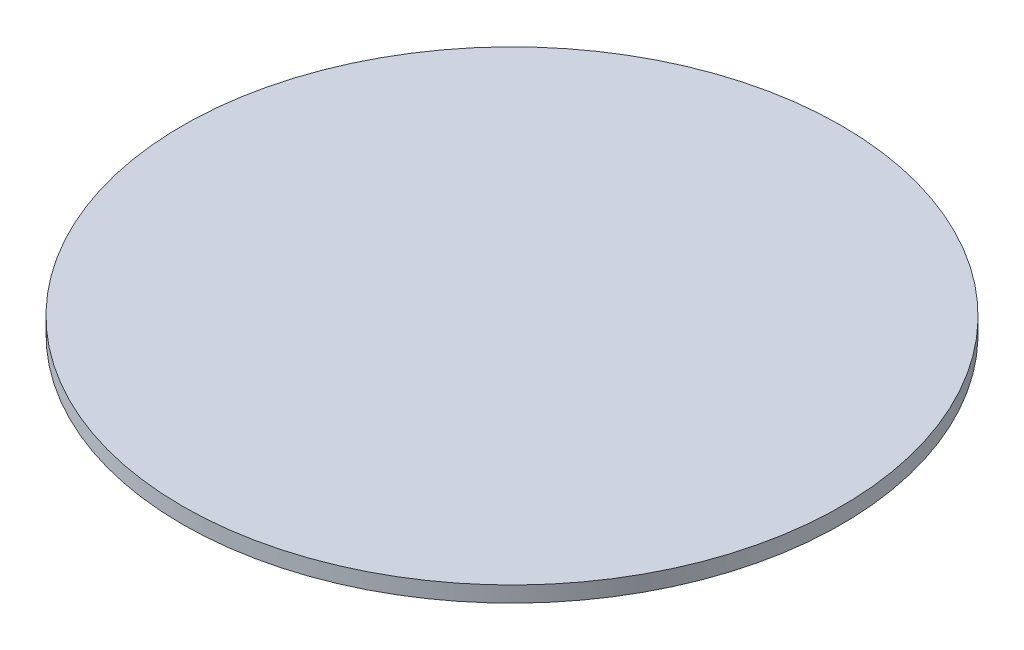
SolidWorks part; units mm, degrees
ref_plane "Front Plane" through (0, 0, 0) normal (0, 0, 1) x (1, 0, 0)
ref_plane "Top Plane" through (0, 0, 0) normal (0, 1, 0) x (1, 0, 0)
ref_plane "Right Plane" through (0, 0, 0) normal (1, 0, 0) x (0, 0, -1)
sketch "Front" plane through (0, 0, 0) normal (0, 0, 1) x (1, 0, 0)
  line L0 (0, 0) -> (0, 13458.9015) construction
  line L1 (0, 0) -> (13458.9015, 0) construction
  line L3 (-20.95, -0.5) -> (0, -0.5)
  line L4 (-20.95, -0.5) -> (-20.95, 0.5)
  line L5 (-20.95, 0.5) -> (0, 0.5)
  line L6 (0, -0.5) -> (0, 0.5)
  line L7 (-20.95, -0.5) -> (0, 0.5) construction
  line L8 (-20.95, 0.5) -> (0, -0.5) construction
  point P5 (-10.475, 0)
  dimension "D1" = 41.9
  dimension "D2" = 1
sketch "Right" plane through (0, 0, 0) normal (1, 0, 0) x (0, 0, -1)
  line L0 (0, 0) -> (0, 50000) construction
  line L1 (0, 0) -> (50000, 0) construction
revolve "Base" add sketch "Front" angle 360 about L0
sketch "Sketch1" plane through (0, -0.5, 0) normal (0, -1, 0) x (1, 0, 0)
  line L0 (0, 0) -> (167.4187, 0) construction
  line L1 (-2, 14.5) -> (-2, 15.5)
  line L2 (-2, 14.5) -> (2, 14.5)
  line L3 (2, 14.5) -> (2, 15.5)
  line L4 (-2, 15.5) -> (2, 15.5)
  line L5 (-2, 14.5) -> (2, 15.5) construction
  line L6 (2, 14.5) -> (-2, 15.5) construction
  line L7 (0, 0) -> (0, -167.4187) construction
  line L8 (2, -14.5) -> (-2, -15.5) construction
  line L9 (-2, -14.5) -> (2, -15.5) construction
  line L10 (-2, -15.5) -> (2, -15.5)
  line L11 (2, -14.5) -> (2, -15.5)
  line L12 (-2, -14.5) -> (2, -14.5)
  line L13 (-2, -14.5) -> (-2, -15.5)
  point P0 (0, 15)
  point P16 (0, -15)
  dimension "D1" = 4
  dimension "D2" = 1
  dimension "D3" = 30
extrude "Holders" add sketch "Sketch1" along normal blind 1.8
sketch "Top" plane through (0, 0, 0) normal (0, 1, 0) x (1, 0, 0)
  line L0 (0, 0) -> (0, 50000) construction
  line L1 (0, 0) -> (50000, 0) construction
  line L2 (-20.95, 0) -> (-20.95, -50000) construction
  line L3 (-11.15, 0.85) -> (-8.85, 0.85)
  line L4 (-11.15, 0.85) -> (-11.15, -0.85)
  line L5 (-11.15, -0.85) -> (-8.85, -0.85)
  line L6 (-8.85, 0.85) -> (-8.85, -0.85)
  line L7 (-11.15, 0.85) -> (-8.85, -0.85) construction
  line L8 (-11.15, -0.85) -> (-8.85, 0.85) construction
  line L9 (48.3333, 187) -> (325.6667, 187) construction
  line L56 (-196.5755, -673.0124) -> (-1063.2422, -673.0124) construction
  line L160 (55, 213) -> (355, 213) construction
  line L179 (246.6667, 830) -> (1313.3333, 830) construction
  circle A0 centre (0, 0) radius 10 construction
  circle A1 centre (0, 0) radius 1
  circle A2 centre (0, 0) radius 20.95 construction
  circle A3 centre (0, 0) radius 20.95 construction
  circle A11 centre (0, 0) radius 20.95
  circle A12 centre (0, 0) radius 20.95
  point P2 (-10, 0)
  line B0 (10.1024, -6.1142) -> (12.9542, -6.1142)
  line B1 (12.9542, -6.1142) -> (13.3534, -5.5108)
  line B2 (13.3534, -5.5108) -> (13.0768, -5.3279) construction
  line B3 (13.0768, -5.3279) -> (12.8294, -5.7019)
  line B4 (12.8294, -5.7019) -> (11.8517, -5.7019)
  line B5 (11.8517, -5.7019) -> (12.5309, -5.2262)
  line B6 (12.5309, -5.2262) -> (12.4417, -5.0731) construction
  line B7 (12.4417, -5.0731) -> (11.1183, -5.7019)
  line B8 (11.1183, -5.7019) -> (10.1024, -5.7019)
  line B9 (10.1024, -5.7019) -> (10.1024, -6.1142) construction
  arc B10 (10.1024, -5.7019) -> (10.1024, -6.1142) centre (10.1024, -5.9081) ccw
  arc B11 (13.0768, -5.3279) -> (13.3534, -5.5108) centre (13.2151, -5.4193) cw
  arc B12 (12.4417, -5.0731) -> (12.5309, -5.2262) centre (12.4799, -5.1534) cw
  line B13 (3.1717, -14.0093) -> (3.0753, -13.5647)
  line B14 (3.0753, -13.5647) -> (3.2831, -13.4679) construction
  line B15 (3.2831, -13.4679) -> (3.544, -13.805)
  line B16 (3.544, -13.805) -> (4.3566, -13.805)
  line B17 (4.3566, -13.805) -> (4.0735, -12.6449)
  line B18 (4.4491, -12.513) -> (5.0512, -13.805)
  line B19 (5.0512, -13.805) -> (5.8587, -13.805)
  line B20 (5.8587, -13.805) -> (6.063, -14.0093) construction
  line B21 (6.063, -14.0093) -> (3.1717, -14.0093) construction
  line B22 (6.063, -14.0093) -> (6.063, -13.805) construction
  line B23 (5.0512, -14.2135) -> (5.8587, -14.2135)
  line B24 (4.4491, -15.5055) -> (5.0512, -14.2135)
  line B25 (4.3566, -14.2135) -> (4.0735, -15.3736)
  line B26 (3.544, -14.2135) -> (4.3566, -14.2135)
  line B27 (3.2831, -14.5506) -> (3.544, -14.2135)
  line B28 (3.1717, -14.0093) -> (3.0753, -14.4538)
  arc B29 (3.0753, -13.5647) -> (3.2831, -13.4679) centre (3.1902, -13.5398) cw
  arc B30 (4.0735, -12.6449) -> (4.4491, -12.513) centre (4.2678, -12.5975) cw
  arc B31 (5.8587, -13.805) -> (5.8587, -14.2135) centre (5.8587, -14.0093) cw
  arc B32 (4.0735, -15.3736) -> (4.4491, -15.5055) centre (4.2678, -15.421) ccw
  arc B33 (3.0753, -14.4538) -> (3.2831, -14.5506) centre (3.1902, -14.4787) ccw
  line B34 (9.4506, -11.1208) -> (10.8266, -11.3161)
  line B35 (9.4506, -11.1208) -> (9.0877, -11.8402)
  line B36 (9.4799, -12.2126) -> (8.9219, -12.3234)
  line B37 (8.8252, -12.3426) -> (9.547, -9.6488) construction
  line B38 (9.6226, -10.5201) -> (9.6744, -9.8283)
  line B39 (9.0877, -11.8402) -> (9.5022, -12.0547)
  line B40 (9.547, -9.6488) -> (9.6942, -9.6883) construction
  line B41 (8.3233, -11.9027) -> (8.7511, -12.2776)
  line B42 (8.849, -11.7763) -> (8.3828, -11.7548)
  line B43 (8.8945, -10.9718) -> (8.849, -11.7763)
  line B44 (8.8945, -10.9718) -> (7.6052, -10.4529)
  line B45 (9.0459, -10.3655) -> (7.7038, -10.1147)
  line B46 (9.0459, -10.3655) -> (9.3469, -9.7406)
  arc B47 (9.3469, -9.7406) -> (9.6744, -9.8283) centre (9.5023, -9.8155) cw
  arc B48 (10.9103, -10.9739) -> (10.8266, -11.3161) centre (10.8515, -11.1409) cw
  arc B49 (9.5022, -12.0547) -> (9.4799, -12.2126) centre (9.4634, -12.1297) cw
  arc B50 (8.3828, -11.7548) -> (8.3233, -11.9027) centre (8.3789, -11.8391) ccw
  arc B51 (7.7038, -10.1147) -> (7.6052, -10.4529) centre (7.6713, -10.2887) ccw
  arc B52 (8.9219, -12.3234) -> (8.7511, -12.2776) centre (8.8829, -12.1272) cw
  line B53 (-14.8048, -9.3788) -> (-10.2337, -9.0018)
  line B54 (-11.4785, -9.6078) -> (-10.1971, -9.5296)
  line B55 (-9.7035, -11.3841) -> (-9.607, -9.9134)
  line B56 (-8.7098, -9.5348) -> (-8.0662, -9.577)
  line B57 (-8.6483, -9.0156) -> (-4.495, -9.3209)
  line B58 (-5.7896, -9.0783) -> (-5.8829, -8.9543)
  line B59 (-5.8829, -8.9543) -> (-6.0138, -8.9543)
  line B60 (-6.0138, -8.9543) -> (-6.0138, -8.9749)
  line B61 (-6.0138, -8.9749) -> (-6.8973, -8.8985)
  line B62 (-6.8973, -8.8985) -> (-6.9571, -8.7559)
  line B63 (-6.9571, -8.7559) -> (-7.074, -8.7559)
  line B64 (-7.074, -8.7559) -> (-7.0917, -8.8809)
  line B65 (-7.0917, -8.8809) -> (-7.5535, -8.841)
  line B66 (-7.5535, -8.841) -> (-7.5535, -8.7852)
  line B67 (-7.7996, -8.7224) -> (-7.7996, -8.7852)
  line B68 (-7.7996, -8.7852) -> (-7.9711, -8.7852)
  line B69 (-7.9711, -8.7852) -> (-7.9715, -8.6313)
  line B70 (-7.9715, -8.6313) -> (-8.0889, -8.6313)
  line B71 (-8.0889, -8.6313) -> (-8.0889, -8.7406)
  line B72 (-8.0889, -8.7406) -> (-8.3186, -8.7111)
  line B73 (-8.3186, -8.7111) -> (-8.3186, -8.1477)
  line B74 (-8.3186, -8.1477) -> (-8.2823, -8.1477)
  line B75 (-8.2823, -8.1477) -> (-8.2823, -8.3009)
  line B76 (-8.2823, -8.3009) -> (-8.1175, -8.3009)
  line B77 (-8.1175, -8.3009) -> (-8.1175, -7.9017)
  line B78 (-8.1175, -7.9017) -> (-8.3103, -7.9017)
  line B79 (-8.3103, -7.9017) -> (-8.3103, -8.0795)
  line B80 (-8.3103, -8.0795) -> (-8.434, -8.0795)
  line B81 (-8.434, -8.0795) -> (-8.434, -7.9017)
  line B82 (-8.434, -7.9017) -> (-8.6122, -7.9017)
  line B83 (-8.6122, -7.9017) -> (-8.6122, -8.3009)
  line B84 (-8.6122, -8.3009) -> (-8.434, -8.3009)
  line B85 (-8.434, -8.3009) -> (-8.434, -8.1477)
  line B86 (-8.434, -8.1477) -> (-8.396, -8.1477)
  line B87 (-8.396, -8.1477) -> (-8.396, -8.7545)
  line B88 (-8.396, -8.7545) -> (-8.7639, -8.6726)
  line B89 (-9.1996, -8.4342) -> (-9.3573, -8.2406)
  line B90 (-9.3573, -8.2406) -> (-9.3573, -7.8977)
  line B91 (-9.3573, -7.8977) -> (-9.3311, -7.8977)
  line B92 (-9.3311, -7.8977) -> (-9.3311, -8.0162)
  line B93 (-9.3311, -8.0162) -> (-9.2067, -8.0162)
  line B94 (-9.2067, -8.0162) -> (-9.2067, -7.708)
  line B95 (-9.2067, -7.708) -> (-9.3311, -7.708)
  line B96 (-9.3311, -7.708) -> (-9.3311, -7.8159)
  line B97 (-9.3311, -7.8159) -> (-9.4502, -7.8159)
  line B98 (-9.4502, -7.8159) -> (-9.4502, -7.708)
  line B99 (-9.4502, -7.708) -> (-9.5764, -7.708)
  line B100 (-9.5764, -7.708) -> (-9.5764, -8.0162)
  line B101 (-9.5764, -8.0162) -> (-9.4502, -8.0162)
  line B102 (-9.4502, -8.0162) -> (-9.4502, -7.8977)
  line B103 (-9.4502, -7.8977) -> (-9.4193, -7.8977)
  line B104 (-9.4193, -7.8977) -> (-9.4264, -8.2406)
  line B105 (-9.4264, -8.2406) -> (-9.5451, -8.4257)
  line B106 (-9.5451, -8.4257) -> (-9.9845, -8.4257)
  line B107 (-10.1971, -8.6436) -> (-10.7436, -8.7688)
  line B108 (-10.7436, -8.7688) -> (-10.7436, -8.1855)
  line B109 (-10.7436, -8.1855) -> (-10.6827, -8.1855)
  line B110 (-10.6827, -8.1855) -> (-10.6827, -8.3154)
  line B111 (-10.6827, -8.3154) -> (-10.5328, -8.3154)
  line B112 (-10.5328, -8.3154) -> (-10.5328, -7.8935)
  line B113 (-10.5328, -7.8935) -> (-10.7179, -7.8935)
  line B114 (-10.7179, -7.8935) -> (-10.7179, -8.0692)
  line B115 (-10.7179, -8.0692) -> (-10.8501, -8.0692)
  line B116 (-10.8501, -8.0692) -> (-10.8501, -7.8935)
  line B117 (-10.8501, -7.8935) -> (-11.0264, -7.8935)
  line B118 (-11.0264, -7.8935) -> (-11.0264, -8.3154)
  line B119 (-11.0264, -8.3154) -> (-10.8663, -8.3154)
  line B120 (-10.8663, -8.3154) -> (-10.8663, -8.1855)
  line B121 (-10.8663, -8.1855) -> (-10.8135, -8.1855)
  line B122 (-10.8135, -8.1855) -> (-10.8135, -8.7962)
  line B123 (-10.8135, -8.7962) -> (-11.0537, -8.8512)
  line B124 (-11.0537, -8.8512) -> (-11.0999, -8.7385)
  line B125 (-11.5154, -8.8512) -> (-11.5154, -8.9415)
  line B126 (-11.5154, -8.9415) -> (-12.1579, -8.9847)
  line B127 (-12.1579, -8.9847) -> (-12.1579, -8.8586)
  line B128 (-12.1579, -8.8586) -> (-12.2777, -8.8586)
  line B129 (-12.2777, -8.8586) -> (-12.3058, -8.9847)
  line B130 (-12.3058, -8.9847) -> (-13.2414, -9.083)
  line B131 (-13.2414, -9.083) -> (-13.2414, -8.9631)
  line B132 (-13.2414, -8.9631) -> (-13.4138, -8.9631)
  line B133 (-13.4138, -8.9631) -> (-13.4138, -9.118)
  line B134 (-13.4138, -9.118) -> (-14.8048, -9.2641)
  line B135 (-14.8048, -9.2641) -> (-14.8048, -9.3788)
  line B136 (-5.7896, -9.0783) -> (-4.495, -9.1903)
  line B137 (-4.495, -9.1903) -> (-4.495, -9.3209)
  line B138 (-11.4785, -9.6078) -> (-11.4785, -9.5427)
  line B139 (-11.4785, -9.5427) -> (-10.2337, -9.3788)
  line B140 (-9.797, -9.8384) -> (-9.797, -11.3629)
  line B141 (-9.797, -11.3629) -> (-9.7035, -11.3841)
  line B142 (-8.6483, -9.43) -> (-8.0662, -9.5348)
  line B143 (-8.0662, -9.5348) -> (-8.0662, -9.577)
  arc B144 (-10.2337, -9.0018) -> (-10.2337, -9.3788) centre (-9.7805, -9.1903) ccw
  arc B145 (-10.1971, -9.5296) -> (-9.797, -9.8384) centre (-9.6564, -9.2426) ccw
  arc B146 (-9.607, -9.9134) -> (-8.7098, -9.5348) centre (-9.3582, -9.2506) ccw
  arc B147 (-8.6483, -9.43) -> (-8.6483, -9.0156) centre (-9.323, -9.2228) ccw
  arc B148 (-7.5535, -8.7852) -> (-7.7996, -8.7224) centre (-7.5866, -8.4012) ccw
  arc B149 (-8.7639, -8.6726) -> (-9.1996, -8.4342) centre (-9.2108, -8.9719) ccw
  arc B150 (-9.9845, -8.4257) -> (-10.1971, -8.6436) centre (-9.9845, -8.6383) ccw
  arc B151 (-11.0999, -8.7385) -> (-11.5154, -8.8512) centre (-11.3895, -8.4928) ccw
  line B152 (-13.0509, -2.8055) -> (-13.0509, -3.9196)
  line B153 (-13.0509, -3.9196) -> (-12.7163, -4.1188)
  line B154 (-12.7163, -4.1188) -> (-12.7163, -3.9223)
  line B155 (-12.7163, -3.9223) -> (-12.4368, -3.9223)
  line B156 (-12.4368, -3.9223) -> (-12.4368, -4.3152)
  line B157 (-12.4368, -4.3152) -> (-12.1223, -4.5025)
  line B158 (-12.1223, -4.5025) -> (-12.1223, -4.2765)
  line B159 (-12.1223, -4.2765) -> (-11.8428, -4.2765)
  line B160 (-11.8428, -4.2765) -> (-11.8428, -4.6904)
  line B161 (-11.8428, -4.6904) -> (-11.5725, -4.8514)
  line B162 (-11.5725, -4.8514) -> (-11.5725, -5.3066)
  line B163 (-11.5725, -5.3066) -> (-12.6251, -4.6798)
  line B164 (-12.6251, -4.6798) -> (-13.0568, -4.6798)
  line B165 (-13.0568, -4.6798) -> (-13.0568, -5.8447)
  line B166 (-13.0568, -5.8447) -> (-12.5305, -6.1641)
  line B167 (-12.5305, -6.1641) -> (-12.5305, -6.4469)
  line B168 (-12.5305, -6.4469) -> (-13.1278, -6.306)
  line B169 (-13.1278, -6.306) -> (-13.1278, -6.5082)
  line B170 (-13.2579, -6.6253) -> (-13.2579, -2.5727) construction
  line B171 (-13.2579, -2.5727) -> (-13.0509, -2.8055)
  line B172 (-13.2579, -6.6253) -> (-13.1278, -6.5082)
  line B173 (-13.2579, -6.6253) -> (-13.388, -6.5082)
  line B174 (-13.388, -6.306) -> (-13.388, -6.5082)
  line B175 (-13.9853, -6.4469) -> (-13.388, -6.306)
  line B176 (-13.9853, -6.1641) -> (-13.9853, -6.4469)
  line B177 (-13.459, -5.8447) -> (-13.9853, -6.1641)
  line B178 (-13.459, -4.6798) -> (-13.459, -5.8447)
  line B179 (-13.8906, -4.6798) -> (-13.459, -4.6798)
  line B180 (-14.9433, -5.3066) -> (-13.8906, -4.6798)
  line B181 (-14.9433, -4.8514) -> (-14.9433, -5.3066)
  line B182 (-14.673, -4.6904) -> (-14.9433, -4.8514)
  line B183 (-14.673, -4.2765) -> (-14.673, -4.6904)
  line B184 (-14.3935, -4.2765) -> (-14.673, -4.2765)
  line B185 (-14.3935, -4.5025) -> (-14.3935, -4.2765)
  line B186 (-14.079, -4.3152) -> (-14.3935, -4.5025)
  line B187 (-14.079, -3.9223) -> (-14.079, -4.3152)
  line B188 (-13.7995, -3.9223) -> (-14.079, -3.9223)
  line B189 (-13.7995, -4.1188) -> (-13.7995, -3.9223)
  line B190 (-13.4649, -3.9196) -> (-13.7995, -4.1188)
  line B191 (-13.4649, -2.8055) -> (-13.4649, -3.9196)
  line B192 (-13.2579, -2.5727) -> (-13.4649, -2.8055)
  line B193 (-4.1501, -13.7292) -> (-4.3367, -14.2275)
  line B194 (-4.3367, -14.2275) -> (-4.9032, -14.8089)
  line B195 (-4.9032, -14.8089) -> (-4.8068, -15.4168)
  line B196 (-4.5666, -15.1704) -> (-4.3401, -15.3911)
  line B197 (-4.3401, -15.3911) -> (-4.7449, -15.8066)
  line B198 (-4.4635, -16.5941) -> (-4.3471, -16.7074)
  line B199 (-4.5664, -16.9324) -> (-4.4831, -17.457)
  line B200 (-4.4831, -17.457) -> (-4.7449, -17.7257)
  line B201 (-4.7449, -17.7257) -> (-5.4549, -15.3911)
  line B202 (-5.4549, -15.3911) -> (-6.6251, -16.4346)
  line B203 (-6.6251, -16.4346) -> (-6.5699, -17.169)
  line B204 (-6.5699, -17.169) -> (-6.7105, -17.2943)
  line B205 (-6.7105, -17.2943) -> (-7.0245, -16.7708)
  line B206 (-7.0245, -16.7708) -> (-7.1255, -16.8609)
  line B207 (-7.1255, -16.8609) -> (-7.2837, -16.8609)
  line B208 (-4.1501, -13.7292) -> (-7.2837, -16.8609) construction
  line B209 (-7.2836, -16.7027) -> (-7.2837, -16.8609)
  line B210 (-7.1935, -16.6018) -> (-7.2836, -16.7027)
  line B211 (-7.7168, -16.2874) -> (-7.1935, -16.6018)
  line B212 (-7.5914, -16.1469) -> (-7.7168, -16.2874)
  line B213 (-6.8571, -16.2026) -> (-7.5914, -16.1469)
  line B214 (-5.8128, -15.033) -> (-6.8571, -16.2026)
  line B215 (-8.147, -14.3216) -> (-5.8128, -15.033)
  line B216 (-7.8781, -14.0599) -> (-8.147, -14.3216)
  line B217 (-7.3536, -14.1435) -> (-7.8781, -14.0599)
  line B218 (-7.1284, -13.9244) -> (-7.3536, -14.1435)
  line B219 (-7.0152, -14.0408) -> (-7.1284, -13.9244)
  line B220 (-7.1534, -14.1754) -> (-7.0152, -14.0408)
  line B221 (-6.2279, -14.3228) -> (-7.1534, -14.1754)
  line B222 (-5.8121, -13.9182) -> (-6.2279, -14.3228)
  line B223 (-5.5915, -14.1449) -> (-5.8121, -13.9182)
  line B224 (-5.8381, -14.3849) -> (-5.5915, -14.1449)
  line B225 (-5.2303, -14.4817) -> (-5.8381, -14.3849)
  line B226 (-4.6485, -13.9155) -> (-5.2303, -14.4817)
  line B227 (-4.1501, -13.7292) -> (-4.6485, -13.9155)
  dimension "D3" = 20
  dimension "D4" = 2
  dimension "D6" = 0
  dimension "D1" = 1.7
  dimension "D2" = 2.3
  dimension "D5" = 9.8
sketch_block_instance "Block1-1"
sketch_block "Block1" parameters "D1"=0.0889, "D2"=0.1658, "D3"=0.2061, "D4"=9.596, "D5"=35.009, "D6"=1.4652, "D7"=0.7235, "D8"=123.485, "D9"=0.9777, "D10"=1.0159, "D11"=2.8519
sketch_block_instance "Block2-1"
sketch_block "Block2"
sketch_block_instance "Block4-1"
sketch_block "Block4"
sketch_block_instance "Block5-1"
sketch_block "Block5"
sketch_block_instance "Block6-1"
sketch_block "Block6"
sketch_block_instance "Block7-1"
sketch_block "Block7"
extrude "Holes Mount & Calendar & Pattern" [suppressed] cut sketch "Top" against normal through all both and the other way through all flip side to cut
